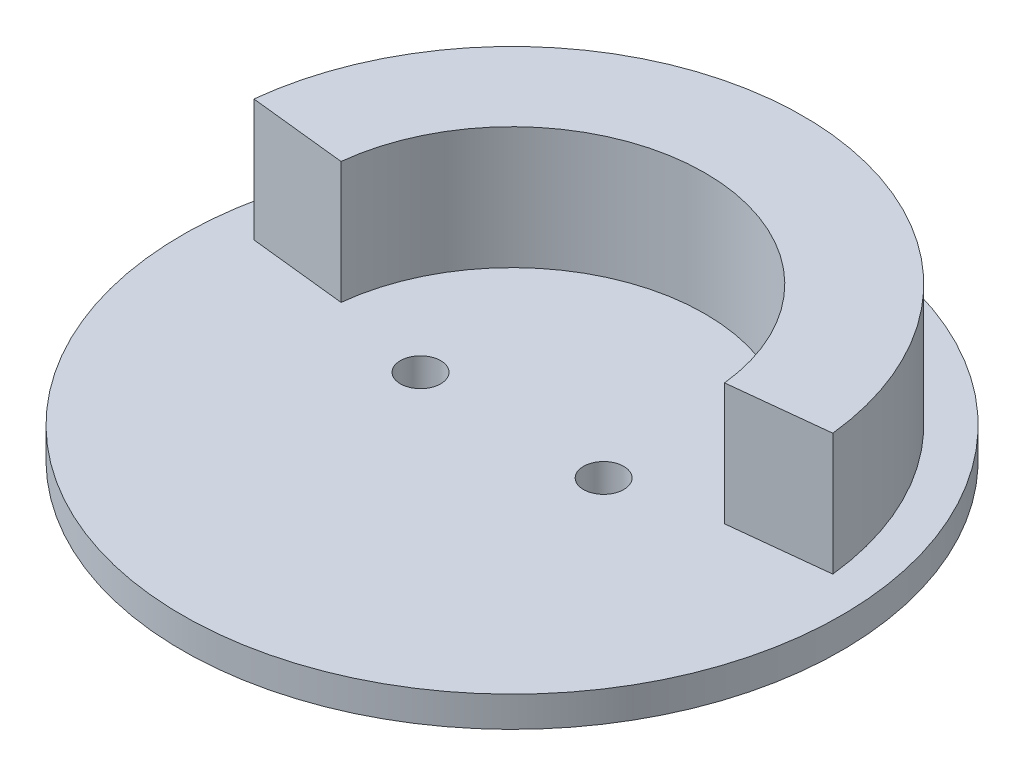
SolidWorks part; units mm, degrees
ref_plane "Front Plane" through (0, 0, 0) normal (0, 0, 1) x (1, 0, 0)
ref_plane "Top Plane" through (0, 0, 0) normal (0, 1, 0) x (1, 0, 0)
ref_plane "Right Plane" through (0, 0, 0) normal (1, 0, 0) x (0, 0, -1)
sketch "Sketch1" plane through (0, 0, 0) normal (0, 1, 0) x (1, 0, 0)
  line L0 (-55, 0) -> (55, 0) construction
  line L1 (-23.7118, 2.5642) -> (-21.1004, 26.712) construction
  line L2 (-23.7118, 2.5642) -> (-15.7084, 1.6987)
  line L3 (0, -55) -> (0, 55) construction
  line L4 (23.7118, 2.5642) -> (15.7084, 1.6987)
  line L5 (-23.32, 5) -> (23.32, 5) construction
  circle A0 centre (0, 0) radius 15.8 construction
  circle A1 centre (0, 0) radius 23.85 construction
  arc A2 (-23.7118, 2.5642) -> (23.7118, 2.5642) centre (0, 0) cw
  arc A3 (-15.7084, 1.6987) -> (15.7084, 1.6987) centre (0, 0) cw
  dimension "D1" = 31.6
  dimension "D2" = 47.7
  dimension "D4" = 5
extrude "Boss-Extrude1" add sketch "Sketch1" along normal blind 10 contours A2 L4 A3 L2
sketch "Sketch2" plane through (0, 0, 0) normal (0, -1, 0) x (1, 0, 0)
  circle A1 centre (0, 0) radius 27
  circle A2 centre (0, 0) radius 3 construction
  dimension "D1" = 54
  dimension "D2" = 6
extrude "Boss-Extrude2" add sketch "Sketch2" along normal blind 2.5
sketch "Sketch3" plane through (0, 0, 0) normal (0, 1, 0) x (1, 0, 0)
  line L0 (-6.875, 0) -> (6.875, 0) construction
  line L1 (0, -6.875) -> (0, 6.875) construction
  circle A0 centre (-7.5, 0) radius 1.65
  circle A1 centre (7.5, 0) radius 1.65
  point P8 (-6.1392, 0)
  dimension "D1" = 3.3
  dimension "D2" = 15
extrude "Cut-Extrude1" cut sketch "Sketch3" against normal blind 10
